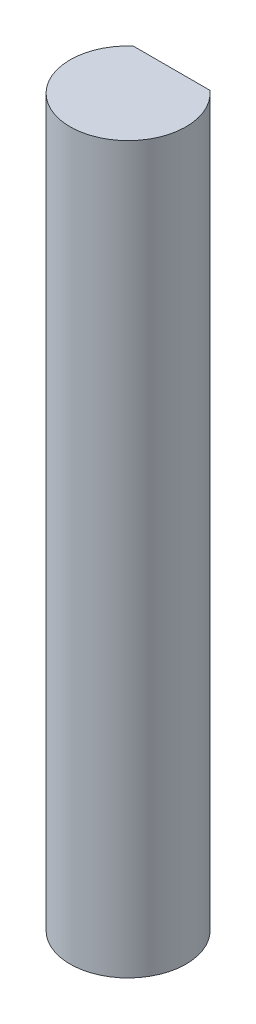
SolidWorks part; units mm, degrees
ref_plane "Front Plane" through (0, 0, 0) normal (0, 0, 1) x (1, 0, 0)
ref_plane "Top Plane" through (0, 0, 0) normal (0, 1, 0) x (1, 0, 0)
ref_plane "Right Plane" through (0, 0, 0) normal (1, 0, 0) x (0, 0, -1)
sketch "Sketch1" plane through (0, 0, 0) normal (0, 1, 0) x (1, 0, 0)
  line L0 (-1.3229, 1.5) -> (1.3229, 1.5)
  arc A0 (-1.3229, 1.5) -> (1.3229, 1.5) centre (0, 0) ccw
  dimension "D1" = 4
  dimension "D2" = 1.5
extrude "Boss-Extrude1" add sketch "Sketch1" along normal blind 25
